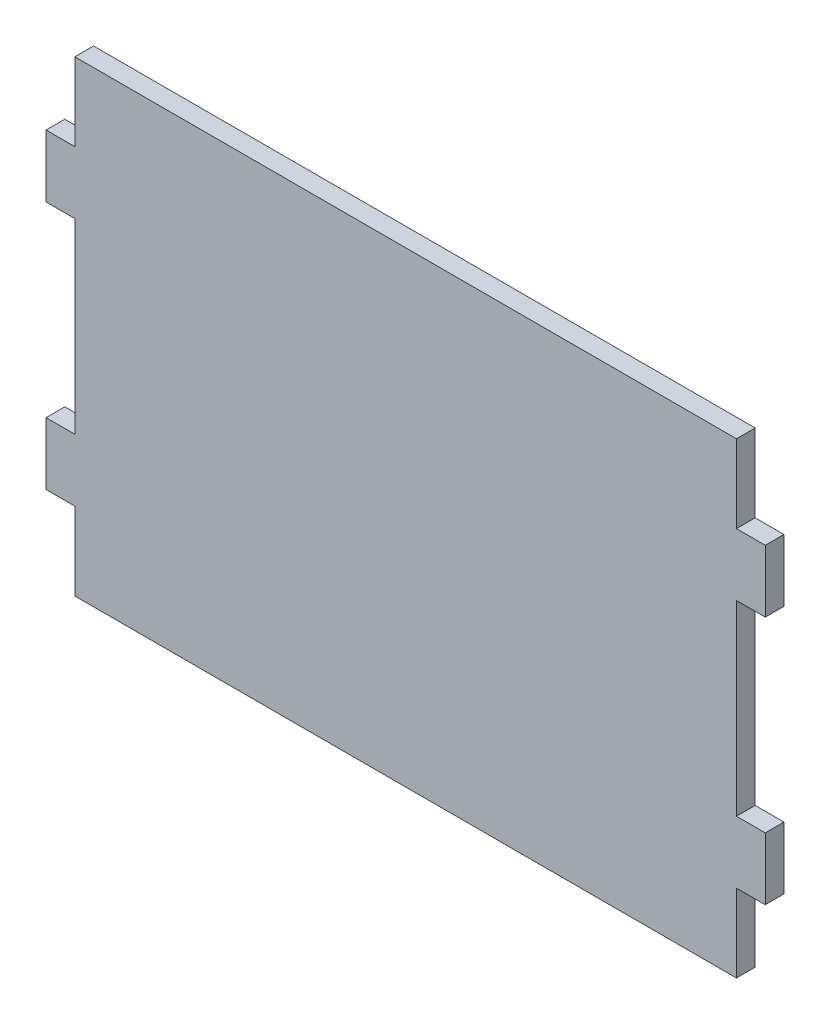
SolidWorks part; units mm, degrees
ref_plane "Спереди" through (0, 0, 0) normal (0, 0, 1) x (1, 0, 0)
ref_plane "Сверху" through (0, 0, 0) normal (0, 1, 0) x (1, 0, 0)
ref_plane "Справа" through (0, 0, 0) normal (1, 0, 0) x (0, 0, -1)
sketch "Sketch1" plane through (0, 0, 0) normal (0, 0, 1) x (1, 0, 0)
  line L0 (212.5, 0) -> (-212.5, 0) construction
  line L1 (-231, -150) -> (231, -150)
  line L2 (-231, -150) -> (-231, 150)
  line L3 (-231, 150) -> (231, 150)
  line L4 (231, -150) -> (231, 150)
  line L5 (-231, -150) -> (231, 150) construction
  line L6 (-231, 150) -> (231, -150) construction
  line L7 (-212.5, -150) -> (-212.5, 150) construction
  line L8 (212.5, -150) -> (212.5, 150) construction
  line L9 (0, 0) -> (0, -47.7117) construction
  line L10 (-212.5, 150) -> (-231, 150)
  line L11 (-212.5, 150) -> (-212.5, 100)
  line L12 (-212.5, 100) -> (-231, 100)
  line L13 (-231, 150) -> (-231, 100)
  line L14 (-212.5, 100) -> (-231, 100)
  line L15 (-212.5, 100) -> (-212.5, 60)
  line L16 (-212.5, 60) -> (-231, 60)
  line L17 (-231, 100) -> (-231, 60)
  line L18 (-212.5, 60) -> (-231, 60)
  line L19 (-212.5, 60) -> (-212.5, -60)
  line L20 (-212.5, -60) -> (-231, -60)
  line L21 (-231, 60) -> (-231, -60)
  line L22 (-212.5, -60) -> (-231, -60)
  line L23 (-212.5, -60) -> (-212.5, -100)
  line L24 (-212.5, -100) -> (-231, -100)
  line L25 (-231, -60) -> (-231, -100)
  line L26 (-231, -150) -> (-212.5, -150)
  line L27 (-231, -150) -> (-231, -100)
  line L28 (-231, -100) -> (-212.5, -100)
  line L29 (-212.5, -150) -> (-212.5, -100)
  line L30 (212.5, 100) -> (231, 100)
  line L31 (231, 150) -> (231, 100)
  line L32 (212.5, 150) -> (231, 150)
  line L33 (212.5, 150) -> (212.5, 100)
  line L34 (212.5, 60) -> (231, 60)
  line L35 (231, 100) -> (231, 60)
  line L36 (212.5, 100) -> (231, 100)
  line L37 (212.5, 100) -> (212.5, 60)
  line L38 (212.5, -60) -> (231, -60)
  line L39 (231, 60) -> (231, -60)
  line L40 (212.5, 60) -> (231, 60)
  line L41 (212.5, 60) -> (212.5, -60)
  line L42 (231, -100) -> (212.5, -100)
  line L43 (212.5, -150) -> (212.5, -100)
  line L44 (231, -150) -> (212.5, -150)
  line L45 (231, -150) -> (231, -100)
  line L46 (212.5, -100) -> (231, -100)
  line L47 (231, -60) -> (231, -100)
  line L48 (212.5, -60) -> (231, -60)
  line L49 (212.5, -60) -> (212.5, -100)
  point P0 (0, 0)
  point P9 (0, 0)
  point P12 (-212.5, 0)
  point P15 (212.5, 0)
  dimension "D1" = 462
  dimension "D2" = 300
  dimension "D3" = 425
  dimension "D4" = 50
  dimension "D5" = 40
  dimension "D6" = 120
  dimension "D7" = 40
extrude "Boss-Extrude1" add sketch "Sketch1" along normal blind 12 contours L49 L41 L37 L33 L3 L11 L15 L19 L23 L29 L1 L43 | L24 L23 L20 L2 | L16 L15 L12 L2 | L30 L37 L34 L4 | L38 L49 L42 L4
